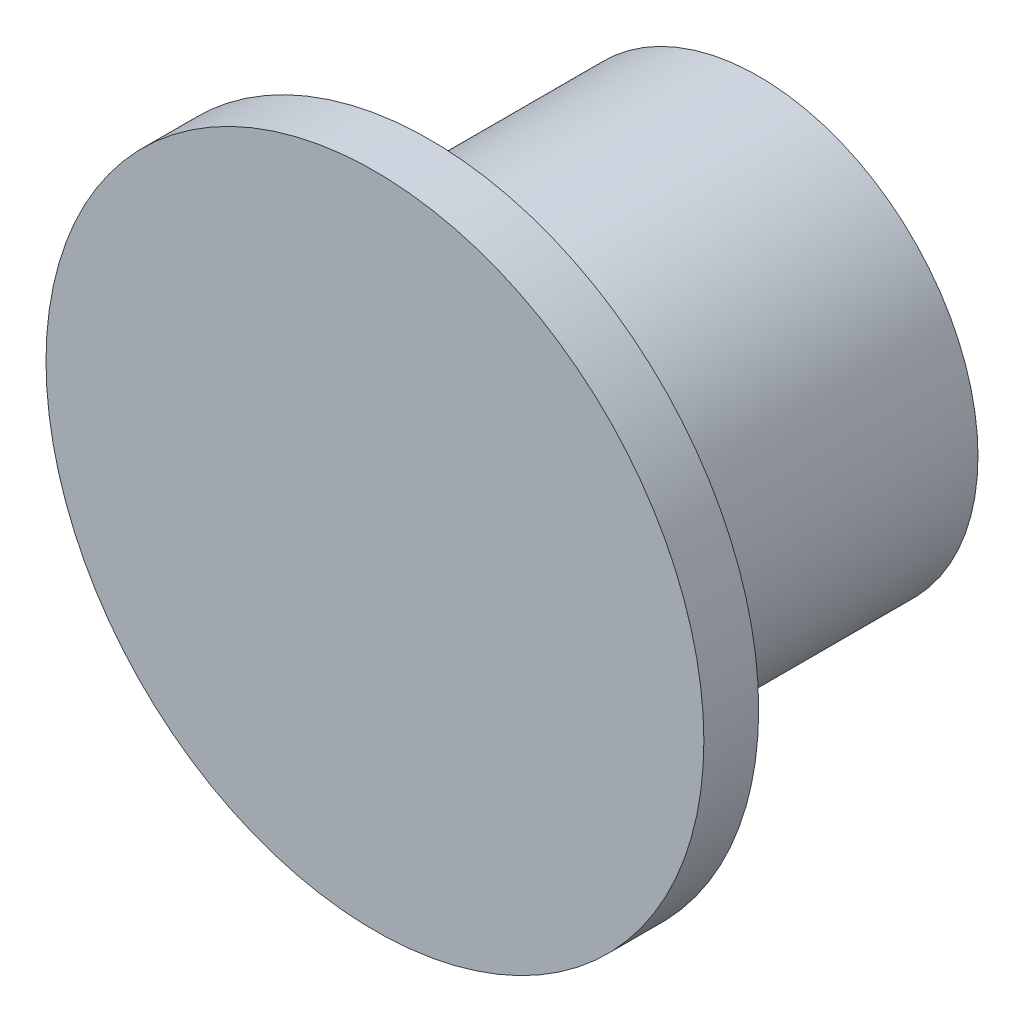
SolidWorks part; units mm, degrees
ref_plane "Alzado" through (0, 0, 0) normal (0, 0, 1) x (1, 0, 0)
ref_plane "Planta" through (0, 0, 0) normal (0, 1, 0) x (1, 0, 0)
ref_plane "Vista lateral" through (0, 0, 0) normal (1, 0, 0) x (0, 0, -1)
sketch "Croquis2" plane through (0, 0, 0) normal (0, 0, 1) x (1, 0, 0)
  circle A0 centre (0, 0) radius 4
extrude "Saliente-Extruir1" add sketch "Croquis2" along normal blind 6
sketch "Croquis3" plane through (0, 0, 6) normal (0, 0, 1) x (1, 0, 0)
  circle A0 centre (0, 0) radius 6
extrude "Saliente-Extruir2" add sketch "Croquis3" along normal blind 1
